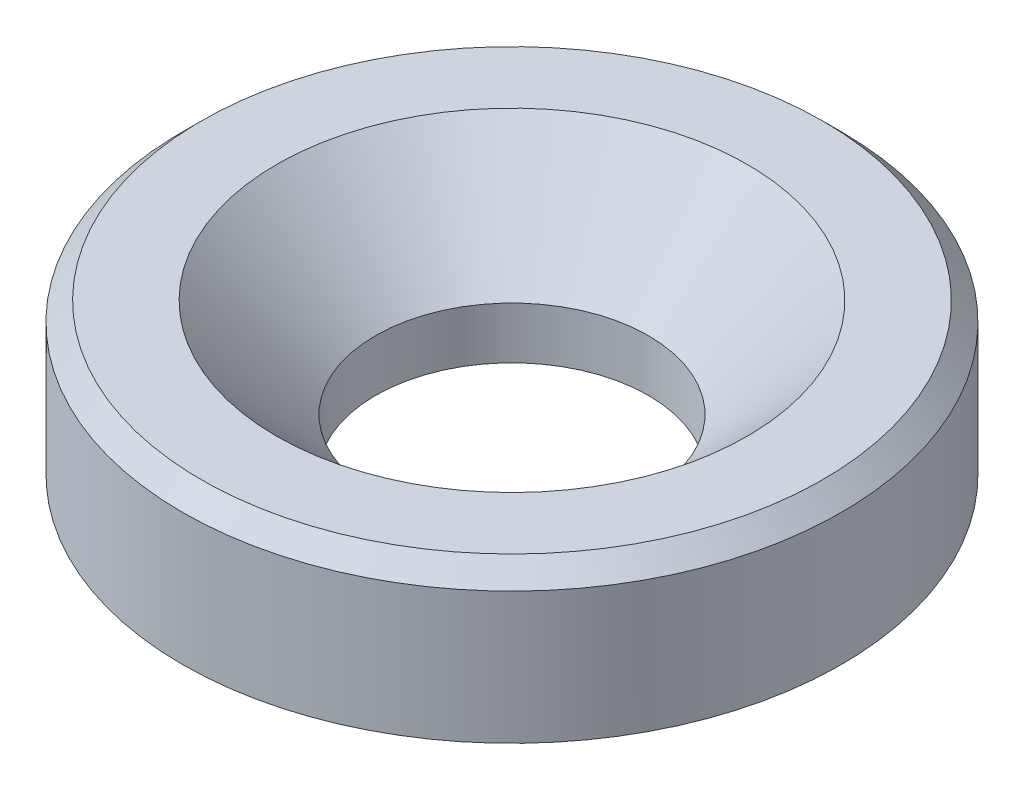
SolidWorks part; units mm, degrees
material "Phosphor bronze 10% D, UNS C52400"
ref_plane "Front Plane" through (0, 0, 0) normal (0, 0, 1) x (1, 0, 0)
ref_plane "Top Plane" through (0, 0, 0) normal (0, 1, 0) x (1, 0, 0)
ref_plane "Right Plane" through (0, 0, 0) normal (1, 0, 0) x (0, 0, -1)
sketch "Sketch2" plane through (0, 0, 0) normal (0, 0, 1) x (1, 0, 0)
  line L0 (0, 11.4523) -> (0, 0) construction
  line L1 (12.5, 8) -> (7.25, 2.75)
  line L2 (7.25, 0) -> (17.5, 0)
  line L3 (17.5, 0) -> (17.5, 8)
  line L4 (17.5, 8) -> (12.5, 8)
  line L5 (7.25, 0) -> (7.25, 2.75)
  dimension "D1" = 8
  dimension "D2" = 35
  dimension "D3" = 45
  dimension "D4" = 25
revolve "Revolve1" add sketch "Sketch2" angle 360 about L0
chamfer "Chamfer1" distance 1 angle 45 1 edges at (0, 8, 17.5)
